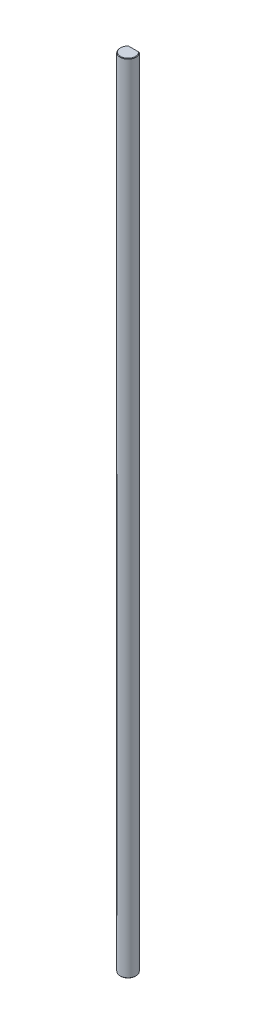
SolidWorks part; units mm, degrees
ref_plane "Front Plane" through (0, 0, 0) normal (0, 0, 1) x (1, 0, 0)
ref_plane "Top Plane" through (0, 0, 0) normal (0, 1, 0) x (1, 0, 0)
ref_plane "Right Plane" through (0, 0, 0) normal (1, 0, 0) x (0, 0, -1)
sketch "Sketch1" plane through (0, 0, 0) normal (0, 1, 0) x (1, 0, 0)
  circle A0 centre (0, 0) radius 4
  dimension "D1" = 8
extrude "Boss-Extrude1" add sketch "Sketch1" along normal blind 400
sketch "Sketch2" plane through (0, 400, 0) normal (0, 1, 0) x (1, 0, 0)
  line L0 (-4, 3) -> (4, 3)
  arc A0 (4, 3) -> (-4, 3) centre (0, 0) ccw
  dimension "D1" = 10
  dimension "D2" = 3
extrude "Cut-Extrude1" cut sketch "Sketch2" against normal through all both and the other way through all
chamfer "Chamfer1" distance 0.25 angle 45 4 edges at (0, 0, -3) (0, 0, 4) (0, 400, -3) (0, 400, 4)
